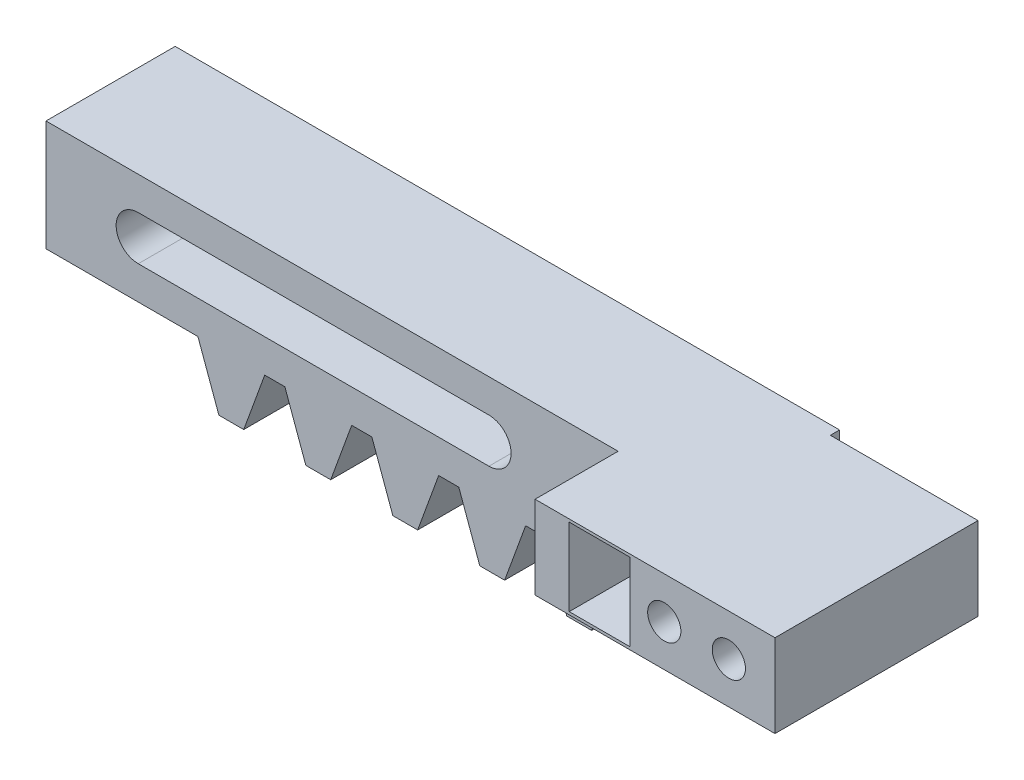
SolidWorks part; units mm, degrees
ref_plane "Front Plane" through (0, 0, 0) normal (0, 0, 1) x (1, 0, 0)
ref_plane "Top Plane" through (0, 0, 0) normal (0, 1, 0) x (1, 0, 0)
ref_plane "Right Plane" through (0, 0, 0) normal (1, 0, 0) x (0, 0, -1)
sketch "Sketch1" plane through (0, 0, 0) normal (0, 0, 1) x (1, 0, 0)
  line L0 (-23, 19.975) -> (13, 19.975)
  line L1 (13, 19.975) -> (13, 13.975)
  line L2 (13, 13.975) -> (7.701, 13.975)
  line L3 (7.701, 13.975) -> (6.5636, 10.85)
  line L4 (6.5636, 10.85) -> (5.2174, 10.85)
  line L5 (5.2174, 10.85) -> (4.0799, 13.975)
  line L6 (4.0799, 13.975) -> (2.9886, 13.975)
  line L7 (2.9886, 13.975) -> (1.8512, 10.85)
  line L8 (1.8512, 10.85) -> (0.505, 10.85)
  line L9 (0.505, 10.85) -> (-0.6324, 13.975)
  line L10 (-0.6324, 13.975) -> (-1.7238, 13.975)
  line L11 (-1.7238, 13.975) -> (-2.8612, 10.85)
  line L12 (-2.8612, 10.85) -> (-4.2074, 10.85)
  line L13 (-4.2074, 10.85) -> (-5.3448, 13.975)
  line L14 (-5.3448, 13.975) -> (-6.4361, 13.975)
  line L15 (-6.4361, 13.975) -> (-7.5735, 10.85)
  line L16 (-7.5735, 10.85) -> (-8.9198, 10.85)
  line L17 (-8.9198, 10.85) -> (-10.0572, 13.975)
  line L18 (-10.0572, 13.975) -> (-11.1485, 13.975)
  line L19 (-11.1485, 13.975) -> (-12.2859, 10.85)
  line L20 (-12.2859, 10.85) -> (-13.6322, 10.85)
  line L21 (-13.6322, 10.85) -> (-14.7696, 13.975)
  line L22 (-14.7696, 13.975) -> (-23, 13.975)
  line L23 (-23, 13.975) -> (-23, 19.975)
extrude "Boss-Extrude1" add sketch "Sketch1" along normal blind 7 from offset 13.5
sketch "Sketch2" plane through (0, 0, 0) normal (0, 0, 1) x (1, 0, 0)
  line L0 (8, 15.475) -> (21, 15.475)
  line L1 (21, 15.475) -> (21, 19.975)
  line L2 (21, 19.975) -> (8, 19.975)
  line L3 (8, 19.975) -> (8, 15.475)
extrude "Boss-Extrude2" add sketch "Sketch2" along normal blind 11 from offset 14
sketch "Sketch3" plane through (0, 0, 0) normal (0, 0, 1) x (1, 0, 0)
  line L0 (9.85, 15.625) -> (13.15, 15.625)
  line L1 (13.15, 15.625) -> (13.15, 19.825)
  line L2 (13.15, 19.825) -> (9.85, 19.825)
  line L3 (9.85, 19.825) -> (9.85, 15.625)
extrude "Cut-Extrude1" cut sketch "Sketch3" along normal blind 3.4 from offset 21.7
sketch "Sketch4" plane through (0, 0, 0) normal (0, 0, 1) x (1, 0, 0)
  circle A0 centre (15, 17.725) radius 0.9
  circle A1 centre (18.5, 17.725) radius 0.9
extrude "Cut-Extrude2" cut sketch "Sketch4" along normal blind 9.1 from offset 16
sketch "Sketch5" plane through (0, 0, 0) normal (0, 0, 1) x (1, 0, 0)
  line L0 (-18, 15.775) -> (1, 15.775)
  line L1 (1, 15.775) -> (1, 18.175)
  line L2 (1, 18.175) -> (-18, 18.175)
  line L3 (-18, 18.175) -> (-18, 15.775)
extrude "Cut-Extrude3" cut sketch "Sketch5" against normal through all and the other way through all
sketch "Sketch6" plane through (0, 0, 0) normal (0, 0, 1) x (1, 0, 0)
  circle A0 centre (-18, 16.975) radius 1.2
  circle A1 centre (1, 16.975) radius 1.2
extrude "Cut-Extrude4" cut sketch "Sketch6" against normal through all and the other way through all
